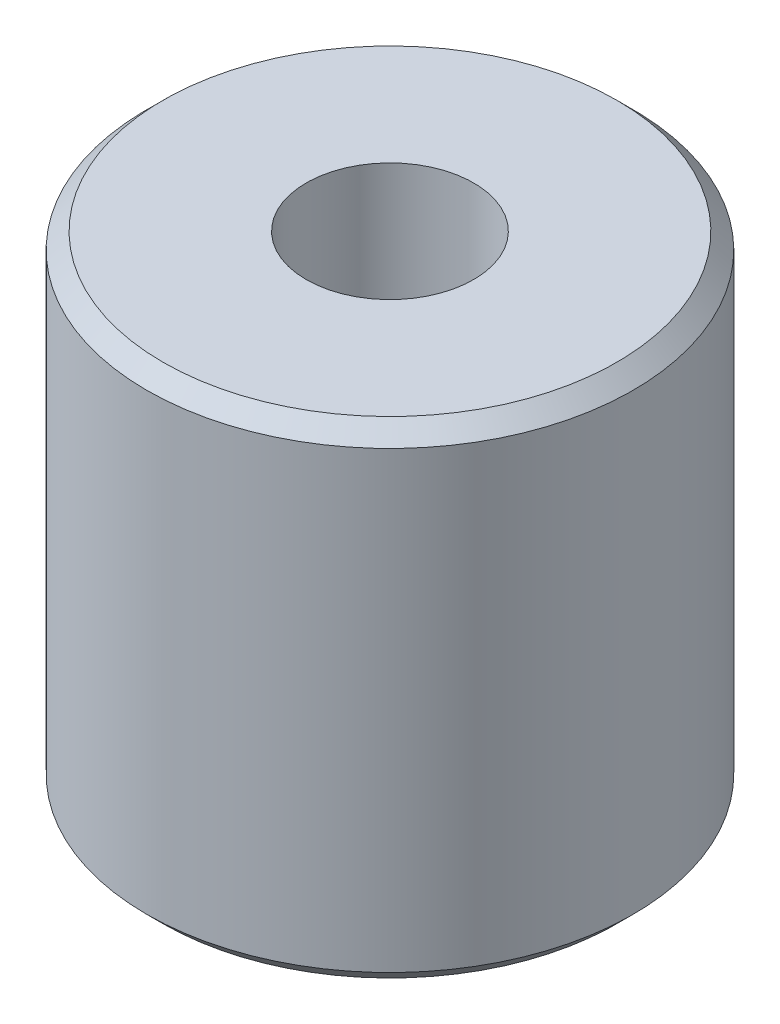
SolidWorks part; units mm, degrees
ref_plane "Alzado" through (0, 0, 0) normal (0, 0, 1) x (1, 0, 0)
ref_plane "Planta" through (0, 0, 0) normal (0, 1, 0) x (1, 0, 0)
ref_plane "Vista lateral" through (0, 0, 0) normal (1, 0, 0) x (0, 0, -1)
sketch "Croquis1" plane through (0, 0, 0) normal (0, 1, 0) x (1, 0, 0)
  circle A0 centre (0, 0) radius 4.5
  dimension "D1" = 9
extrude "Saliente-Extruir1" add sketch "Croquis1" along normal blind 9
chamfer "Chaflán1" distance 0.3 angle 45 1 edges at (0, 9, 4.5)
chamfer "Chaflán2" distance 0.3 angle 45 1 edges at (0, 0, 4.5)
sketch "Croquis2" plane through (0, 9, 0) normal (0, 1, 0) x (1, 0, 0)
  circle A0 centre (0, 0) radius 1.55
extrude "Cortar-Extruir1" cut sketch "Croquis2" against normal blind 9
